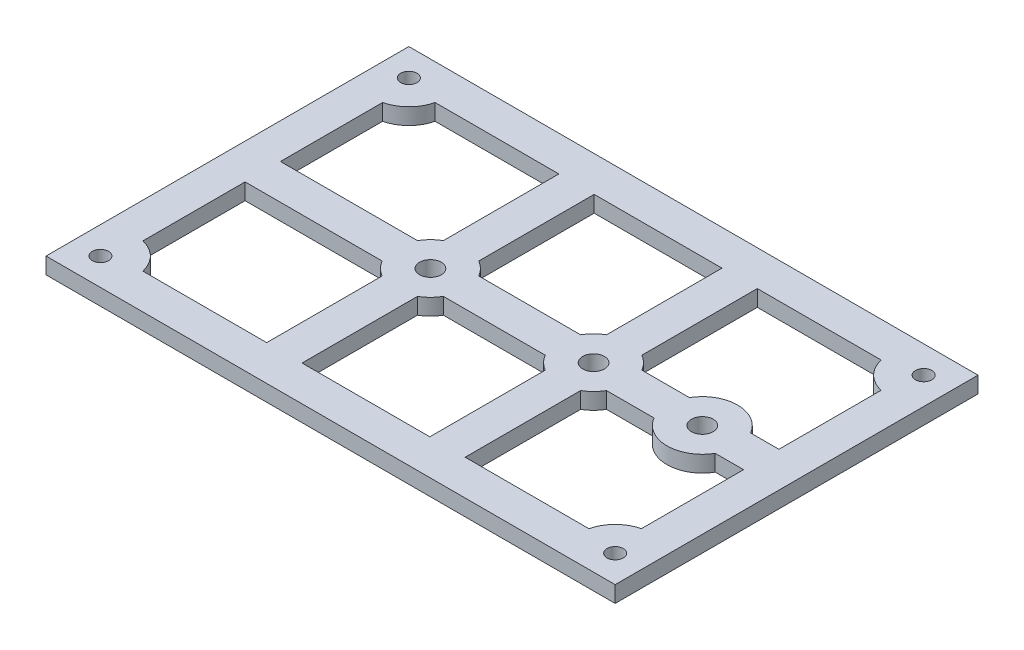
SolidWorks part; units mm, degrees
ref_plane "Front Plane" through (0, 0, 0) normal (0, 0, 1) x (1, 0, 0)
ref_plane "Top Plane" through (0, 0, 0) normal (0, 1, 0) x (1, 0, 0)
ref_plane "Right Plane" through (0, 0, 0) normal (1, 0, 0) x (0, 0, -1)
sketch "Sketch1" plane through (0, 0, 0) normal (0, 1, 0) x (1, 0, 0)
  line L0 (35, 0) -> (33, 0) construction
  line L1 (-52.3364, -33.3645) -> (52.3364, -33.3645)
  line L2 (-52.3364, -33.3645) -> (-52.3364, 33.3645)
  line L3 (-52.3364, 33.3645) -> (52.3364, 33.3645)
  line L4 (52.3364, -33.3645) -> (52.3364, 33.3645)
  line L5 (0, 33.3645) -> (0, 29.5409) construction
  line L6 (-19.756, 33.3645) -> (-19.756, 26.8645) construction
  line L7 (40.6292, -3.25) -> (45.8364, -3.25)
  line L8 (0, -33.3645) -> (-15, -33.3645) construction
  line L9 (-52.3364, 33.3645) -> (-47.3364, 33.3645) construction
  line L10 (-47.3364, 29.8645) -> (-47.3364, 28.3645) construction
  line L12 (-18.25, -26.8645) -> (-18.25, -5.6292)
  line L14 (-11.75, -26.8645) -> (-11.75, -5.6292)
  line L15 (40.6292, 3.25) -> (45.8364, 3.25)
  line L16 (45.8364, 3.25) -> (45.8364, 22.0399)
  line L18 (-23.6478, -33.3645) -> (-23.6478, -26.8645) construction
  line L21 (11.75, -26.8645) -> (11.75, -5.6292)
  line L23 (18.25, -26.8645) -> (18.25, -5.6292)
  line L24 (-11.75, 26.8645) -> (11.75, 26.8645)
  line L25 (18.25, 26.8645) -> (41.0119, 26.8645)
  line L26 (11.75, -26.8645) -> (-11.75, -26.8645)
  line L27 (-45.8364, -3.25) -> (-20.6292, -3.25)
  line L29 (-45.8364, 3.25) -> (-20.6292, 3.25)
  line L31 (20.6292, -3.25) -> (29.3708, -3.25)
  line L32 (45.8364, -3.25) -> (45.8364, -22.0399)
  line L34 (-18.25, 26.8645) -> (-41.0119, 26.8645)
  line L35 (-45.8364, 6.7719) -> (-45.8364, 3.25)
  line L36 (20.6292, 3.25) -> (29.3708, 3.25)
  line L37 (18.25, 5.6292) -> (18.25, 26.8645)
  line L38 (-18.25, 5.6292) -> (-18.25, 26.8645)
  line L39 (11.75, 5.6292) -> (11.75, 26.8645)
  line L40 (18.25, -26.8645) -> (41.0119, -26.8645)
  line L41 (-9.3708, -3.25) -> (9.3708, -3.25)
  line L42 (-18.25, -26.8645) -> (-41.0119, -26.8645)
  line L43 (-45.8364, -3.25) -> (-45.8364, -22.0399)
  line L44 (17, 0) -> (15, 0) construction
  line L45 (-45.8364, 6.7719) -> (-45.8364, 22.0399)
  line L46 (-9.3708, 3.25) -> (9.3708, 3.25)
  line L47 (-11.75, 5.6292) -> (-11.75, 26.8645)
  circle A0 centre (35, 0) radius 2
  circle A1 centre (15, 0) radius 2
  circle A2 centre (-15, 0) radius 2
  arc A3 (-20.6292, -3.25) -> (-18.25, -5.6292) centre (-15, 0) ccw
  arc A5 (29.3708, -3.25) -> (40.6292, -3.25) centre (35, 0) ccw
  circle A6 centre (-47.3364, 28.3645) radius 1.5
  circle A7 centre (47.3364, 28.3645) radius 1.5
  circle A8 centre (-47.3364, -28.3645) radius 1.5
  circle A9 centre (47.3364, -28.3645) radius 1.5
  arc A10 (45.8364, -22.0399) -> (41.0119, -26.8645) centre (47.3364, -28.3645) ccw
  arc A11 (-45.8364, -22.0399) -> (-41.0119, -26.8645) centre (-47.3364, -28.3645) cw
  arc A12 (45.8364, 22.0399) -> (41.0119, 26.8645) centre (47.3364, 28.3645) cw
  arc A13 (-45.8364, 22.0399) -> (-41.0119, 26.8645) centre (-47.3364, 28.3645) ccw
  arc A14 (-9.3708, 3.25) -> (-11.75, 5.6292) centre (-15, 0) ccw
  arc A15 (-18.25, 5.6292) -> (-20.6292, 3.25) centre (-15, 0) ccw
  arc A16 (9.3708, -3.25) -> (11.75, -5.6292) centre (15, 0) ccw
  arc A17 (18.25, -5.6292) -> (20.6292, -3.25) centre (15, 0) ccw
  arc A18 (11.75, 5.6292) -> (9.3708, 3.25) centre (15, 0) ccw
  arc A19 (20.6292, 3.25) -> (18.25, 5.6292) centre (15, 0) ccw
  arc A20 (-11.75, -5.6292) -> (-9.3708, -3.25) centre (-15, 0) ccw
  arc A21 (40.6292, 3.25) -> (29.3708, 3.25) centre (35, 0) ccw
  point P0 (0, 0)
  point P48 (0, 0)
  dimension "D3" = 4
  dimension "D4" = 4
  dimension "D5" = 4
  dimension "D7" = 13
  dimension "D10" = 3
  dimension "D11" = 13
  dimension "D1" = 20
  dimension "D2" = 30
  dimension "D6" = 15
  dimension "D8" = 5
  dimension "D9" = 5
  dimension "D12" = 6.5
  dimension "D14" = 6.5
extrude "Boss-Extrude1" add sketch "Sketch1" along normal blind 3
